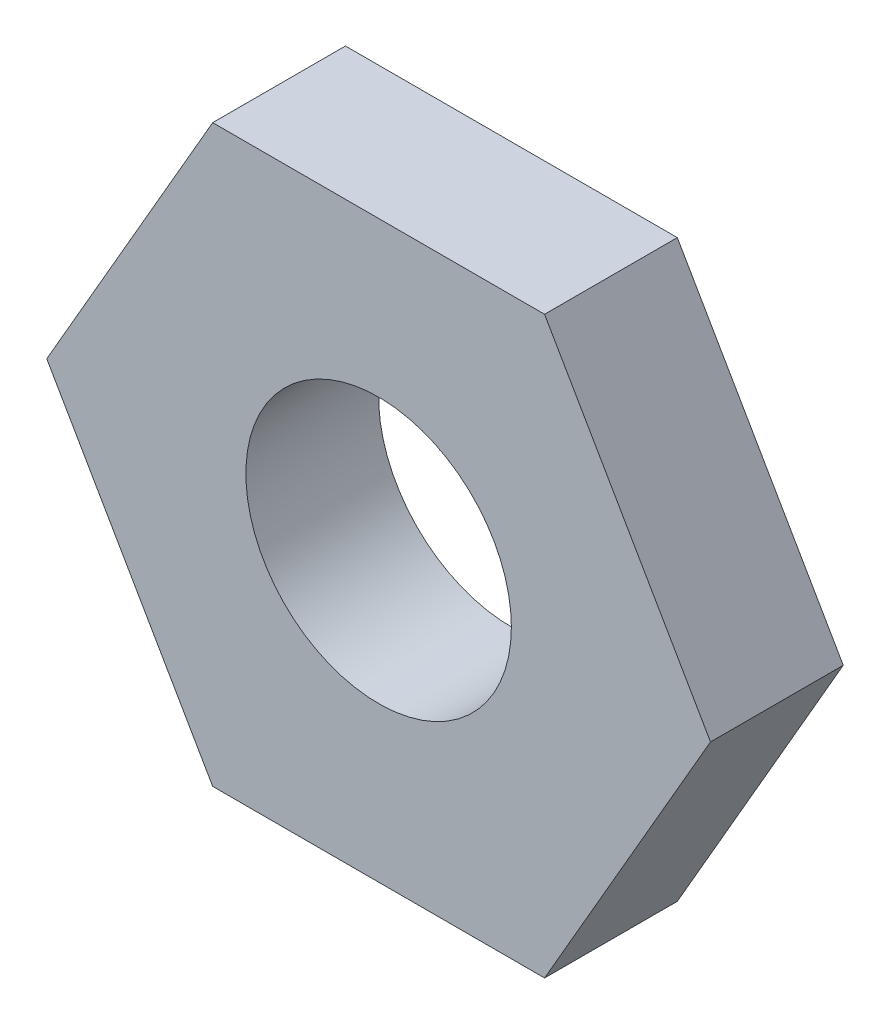
SolidWorks part; units mm, degrees
ref_plane "Front" through (0, 0, 0) normal (0, 0, 1) x (1, 0, 0)
ref_plane "Top" through (0, 0, 0) normal (0, 1, 0) x (1, 0, 0)
ref_plane "Right" through (0, 0, 0) normal (1, 0, 0) x (0, 0, -1)
other "Configuration Table"
sketch "Sketch1" plane through (0, 0, 0) normal (0, 0, 1) x (1, 0, 0)
  line L1 (5, 8.6603) -> (-5, 8.6603)
  line L2 (-5, 8.6603) -> (-10, 0)
  line L3 (-10, 0) -> (-5, -8.6603)
  line L4 (-5, -8.6603) -> (5, -8.6603)
  line L5 (5, -8.6603) -> (10, 0)
  line L6 (10, 0) -> (5, 8.6603)
  circle A0 centre (0, 0) radius 8.6603 construction
  dimension "D1" = 10
extrude "Boss-Extrude1" add sketch "Sketch1" along normal blind 4
sketch "Sketch2" plane through (0, 0, 4) normal (0, 0, 1) x (1, 0, 0)
  circle A0 centre (0, 0) radius 4
  dimension "D1" = 8
extrude "Cut-Extrude1" cut sketch "Sketch2" against normal through all
